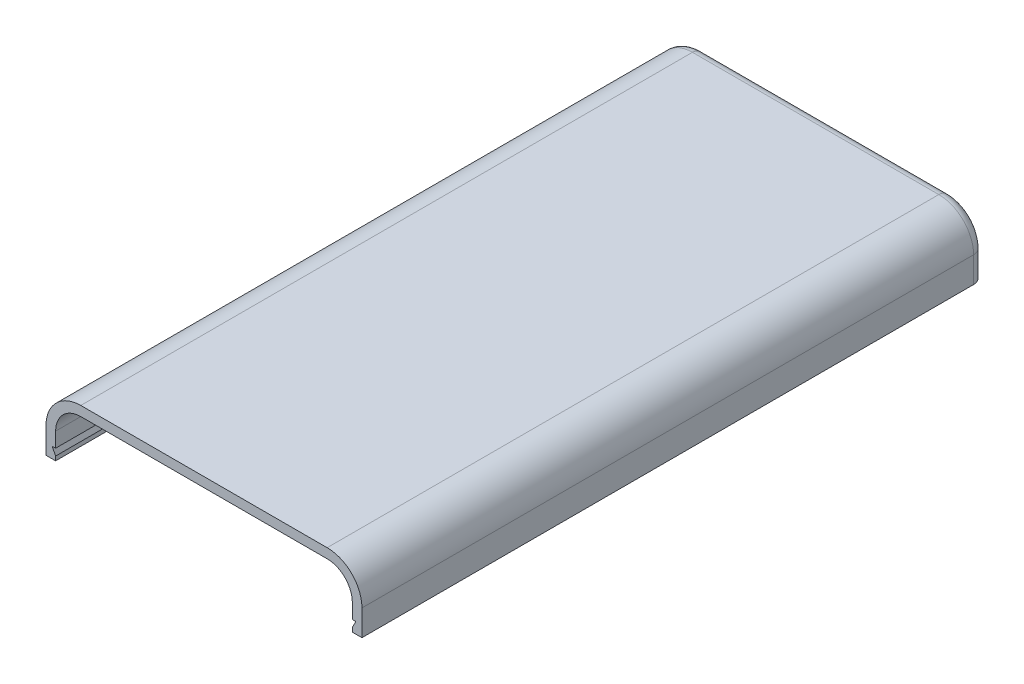
SolidWorks part; units mm, degrees
ref_plane "Front Plane" through (0, 0, 0) normal (0, 0, 1) x (1, 0, 0)
ref_plane "Top Plane" through (0, 0, 0) normal (0, 1, 0) x (1, 0, 0)
ref_plane "Right Plane" through (0, 0, 0) normal (1, 0, 0) x (0, 0, -1)
sketch "Sketch1" plane through (0, 0, 0) normal (0, 0, 1) x (1, 0, 0)
  line L0 (0, 0) -> (59.04, 0)
  line L1 (0, 0) -> (0, 4.82)
  line L2 (59.04, 0) -> (59.04, 4.82)
  line L3 (6.5, 11.32) -> (52.54, 11.32)
  arc A0 (0, 4.82) -> (6.5, 11.32) centre (6.5, 4.82) cw
  arc A1 (59.04, 4.82) -> (52.54, 11.32) centre (52.54, 4.82) ccw
  point P7 (0, 11.32)
  point P10 (59.04, 11.32)
  dimension "D3" = 6.5
  dimension "D1" = 11.32
  dimension "D2" = 59.04
extrude "Boss-Extrude1" add sketch "Sketch1" along normal blind 116.3
sketch "Sketch2" plane through (0, 0, 116.3) normal (0, 0, 1) x (1, 0, 0)
  line L11 (1.8, 2.05) -> (1.145, 2.05)
  line L12 (57.24, 0) -> (57.24, 4.82)
  line L13 (1.8, 4.82) -> (1.8, 0)
  line L14 (52.54, 9.52) -> (6.5, 9.52)
  line L15 (57.24, 0) -> (57.24, 4.82)
  line L16 (1.8, 4.82) -> (1.8, 0)
  line L17 (52.54, 9.52) -> (6.5, 9.52)
  line L18 (1.145, 2.05) -> (1.8, 0.78)
  line L19 (57.24, 2.05) -> (57.895, 2.05)
  line L20 (57.895, 2.05) -> (57.24, 0.78)
  line L21 (0, 4.82) -> (0, 0) construction
  line L22 (59.04, 0) -> (59.04, 4.82) construction
  line L23 (0, 0) -> (59.04, 0) construction
  line L24 (1.8, 0) -> (57.24, 0)
  arc A8 (57.24, 4.82) -> (52.54, 9.52) centre (52.54, 4.82) ccw
  arc A9 (6.5, 9.52) -> (1.8, 4.82) centre (6.5, 4.82) ccw
  arc A10 (57.24, 4.82) -> (52.54, 9.52) centre (52.54, 4.82) ccw
  arc A11 (6.5, 9.52) -> (1.8, 4.82) centre (6.5, 4.82) ccw
  line M9 (0, 0) -> (59.04, 0)
  dimension "D2" = 1.145
  dimension "D3" = 1.145
  dimension "D4" = 1.27
  dimension "D5" = 2.05
  dimension "D1" = 1.8
extrude "Cut-Extrude1" cut sketch "Sketch2" against normal offset from surface (112.7 mm away) 3.6 contours L17 A11 L16 L15 A10 M9 | L20 L19 L15 | L11 L18 L16 up to face at (29.52, 5.8287, 0)
fillet "Fillet1" radius 2 5 edges at (0, 2.41, 0) (1.9038, 9.4162, 0) (29.52, 11.32, 0) (57.1362, 9.4162, 0) (59.04, 2.41, 0)
